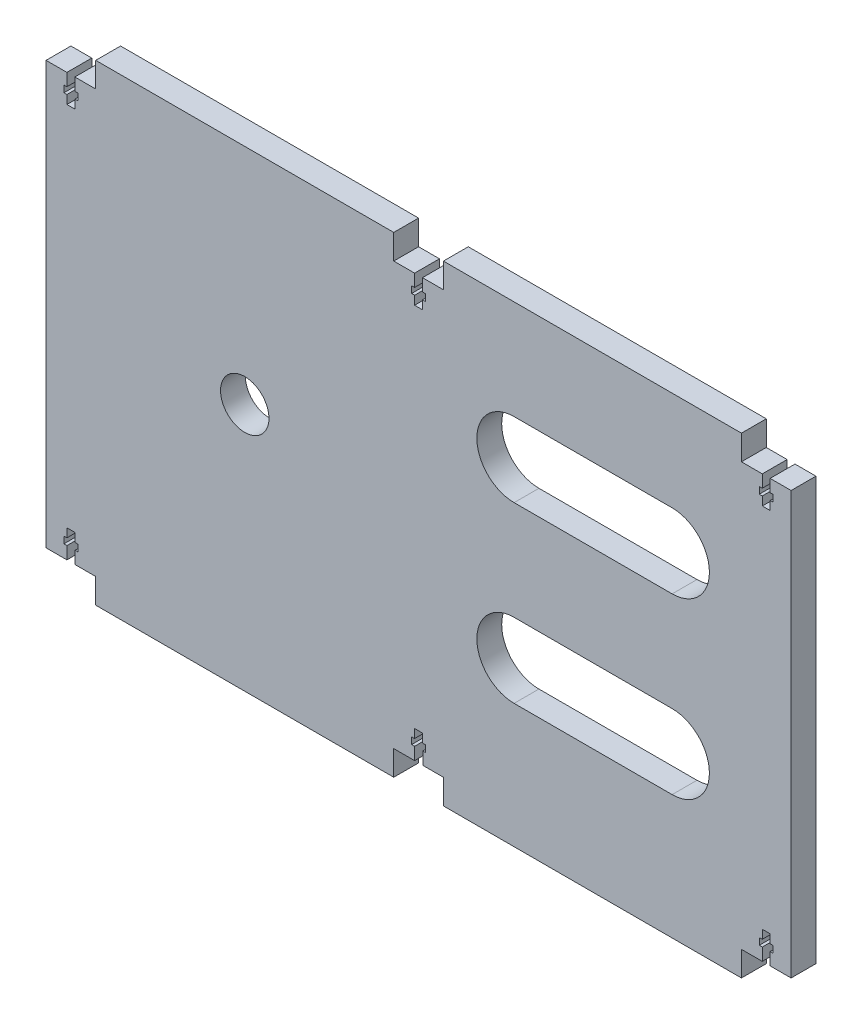
SolidWorks part; units mm, degrees
ref_plane "Ön Düzlem" through (0, 0, 0) normal (0, 0, 1) x (1, 0, 0)
ref_plane "Üst Düzlem" through (0, 0, 0) normal (0, 1, 0) x (1, 0, 0)
ref_plane "Sağ Düzlem" through (0, 0, 0) normal (1, 0, 0) x (0, 0, -1)
sketch "Çizim1" plane through (0, 0, 0) normal (0, 0, 1) x (1, 0, 0)
  line L1 (-150, -90) -> (150, -90)
  line L2 (-150, -90) -> (-150, 90)
  line L3 (-150, 90) -> (150, 90)
  line L4 (150, -90) -> (150, 90)
  line L5 (-150, -90) -> (150, 90) construction
  line L6 (-150, 90) -> (150, -90) construction
  circle A1 centre (-70, 10) radius 9.75
  point P0 (0, 0)
  dimension "D3" = 100
  dimension "D1" = 80
  dimension "D2" = 180
extrude "Yükseklik-Ekstrüzyon1" add sketch "Çizim1" along normal blind 10
sketch "Çizim2" plane through (0, 90, 0) normal (0, 1, 0) x (1, 0, 0)
  line L0 (130, -10) -> (130, 0)
  line L1 (130, -10) -> (10, -10)
  line L2 (130, 0) -> (10, 0)
  line L3 (10, -10) -> (10, 0)
  line L4 (150, -10) -> (-150, -10) construction
  line L5 (150, 0) -> (-150, 0) construction
  line L6 (150, -10) -> (150, 0) construction
  line L7 (-10, 0) -> (-10, -10)
  line L8 (-10, 0) -> (-130, 0)
  line L9 (-10, -10) -> (-130, -10)
  line L10 (-130, 0) -> (-130, -10)
  line L11 (-150, -10) -> (-150, 0) construction
  point P10 (0, 0)
  point P17 (0, 0)
  dimension "D1" = 20
  dimension "D2" = 10
  dimension "D3" = 20
  dimension "D4" = 10
extrude "Yükseklik-Ekstrüzyon2" add sketch "Çizim2" along normal blind 10
sketch "Çizim3" plane through (0, -90, 0) normal (0, -1, 0) x (-1, 0, 0)
  line L0 (150, -10) -> (150, 0)
  line L1 (150, -10) -> (130, -10)
  line L2 (150, 0) -> (130, 0)
  line L3 (130, -10) -> (130, 0)
  line L4 (-150, -10) -> (-150, 0)
  line L5 (-150, -10) -> (-130, -10)
  line L6 (-150, 0) -> (-130, 0)
  line L7 (-130, -10) -> (-130, 0)
  line L8 (10, 0) -> (10, -10)
  line L9 (10, 0) -> (-10, 0)
  line L10 (10, -10) -> (-10, -10)
  line L11 (-10, 0) -> (-10, -10)
  line L12 (150, 0) -> (-150, 0) construction
  line L13 (150, -10) -> (-150, -10) construction
  dimension "D1" = 120
  dimension "D2" = 20
  dimension "D3" = 20
  dimension "D4" = 20
extrude "Kes-Ekstrüzyon1" cut sketch "Çizim3" against normal blind 10
sketch "Çizim4" plane through (0, 0, 10) normal (0, 0, 1) x (1, 0, 0)
  line L0 (-142.8, 85) -> (-137.2, 85)
  line L1 (-142.8, 85) -> (-142.8, 82.3)
  line L2 (-137.2, 85) -> (-137.2, 82.3)
  line L3 (-142.8, 82.3) -> (-137.2, 82.3)
  line L4 (-130, 90) -> (-150, 90) construction
  line L5 (-10, 100) -> (-10, 90) construction
  line L6 (-2.8, 85) -> (2.8, 85)
  line L7 (-2.8, 85) -> (-2.8, 82.3)
  line L8 (-2.8, 82.3) -> (2.8, 82.3)
  line L9 (137.2, 85) -> (142.8, 85)
  line L10 (137.2, 85) -> (137.2, 82.3)
  line L11 (137.2, 82.3) -> (142.8, 82.3)
  line L12 (142.8, 85) -> (142.8, 82.3)
  line L13 (-130, -80) -> (-150, -80) construction
  line L14 (-142.8, -75) -> (-137.2, -75)
  line L15 (-142.8, -75) -> (-142.8, -72.3)
  line L16 (-142.8, -72.3) -> (-137.2, -72.3)
  line L17 (10, -80) -> (10, -90) construction
  line L18 (-2.8, -72.3) -> (2.8, -72.3)
  line L19 (-2.8, -72.3) -> (-2.8, -75)
  line L20 (-2.8, -75) -> (2.8, -75)
  line L21 (2.8, -72.3) -> (2.8, -75)
  line L22 (137.2, -72.3) -> (142.8, -72.3)
  line L23 (137.2, -72.3) -> (137.2, -75)
  line L24 (137.2, -75) -> (142.8, -75)
  line L25 (-150, 90) -> (-150, -80) construction
  line L27 (2.8, 85) -> (2.8, 82.3)
  line L28 (150, -80) -> (150, 90) construction
  line L29 (-137.2, -75) -> (-137.2, -72.3)
  line L30 (142.8, -72.3) -> (142.8, -75)
  dimension "D1" = 5
  dimension "D2" = 7.2
  dimension "D3" = 5.6
  dimension "D4" = 7.2
  dimension "D5" = 5.6
  dimension "D6" = 7.2
  dimension "D7" = 2.7
  dimension "D8" = 2.7
  dimension "D9" = 5
  dimension "D10" = 2.7
  dimension "D11" = 5.6
  dimension "D12" = 2.7
  dimension "D13" = 5.6
  dimension "D14" = 7.2
  dimension "D15" = 7.2
  dimension "D16" = 5.6
  dimension "D17" = 7.2
  dimension "D18" = 5.6
extrude "Kes-Ekstrüzyon2" cut sketch "Çizim4" against normal blind 10
sketch "Çizim5" plane through (0, 0, 10) normal (0, 0, 1) x (1, 0, 0)
  line L0 (-141.6, 82.3) -> (-138.4, 82.3)
  line L1 (-141.6, 82.3) -> (-141.6, 78.8)
  line L2 (-138.4, 82.3) -> (-138.4, 78.8)
  line L3 (-141.6, 78.8) -> (-138.4, 78.8)
  line L4 (-142.8, 82.3) -> (-137.2, 82.3) construction
  line L5 (-1.6, 82.3) -> (1.6, 82.3)
  line L6 (-1.6, 82.3) -> (-1.6, 78.8)
  line L7 (1.6, 82.3) -> (1.6, 78.8)
  line L8 (-1.6, 78.8) -> (1.6, 78.8)
  line L9 (-2.8, 82.3) -> (2.8, 82.3) construction
  line L10 (138.4, 82.3) -> (141.6, 82.3)
  line L11 (138.4, 82.3) -> (138.4, 78.8)
  line L12 (141.6, 82.3) -> (141.6, 78.8)
  line L13 (138.4, 78.8) -> (141.6, 78.8)
  line L14 (150, -80) -> (150, 90) construction
  line L15 (137.2, 82.3) -> (142.8, 82.3) construction
  line L16 (-141.6, -72.3) -> (-138.4, -72.3)
  line L17 (-141.6, -72.3) -> (-141.6, -68.8)
  line L18 (-138.4, -72.3) -> (-138.4, -68.8)
  line L19 (-141.6, -68.8) -> (-138.4, -68.8)
  line L20 (-137.2, -72.3) -> (-142.8, -72.3) construction
  line L21 (-1.6, -72.3) -> (1.6, -72.3)
  line L22 (-1.6, -72.3) -> (-1.6, -68.8)
  line L23 (1.6, -72.3) -> (1.6, -68.8)
  line L24 (-1.6, -68.8) -> (1.6, -68.8)
  line L25 (-1.6, 85) -> (-1.6, 90)
  line L26 (2.8, -72.3) -> (-2.8, -72.3) construction
  line L27 (138.4, -72.3) -> (141.6, -72.3)
  line L28 (138.4, -72.3) -> (138.4, -68.8)
  line L29 (141.6, -72.3) -> (141.6, -68.8)
  line L30 (138.4, -68.8) -> (141.6, -68.8)
  line L31 (-141.6, 85) -> (-138.4, 85)
  line L32 (142.8, -72.3) -> (137.2, -72.3) construction
  line L33 (-141.6, 85) -> (-141.6, 90.0914)
  line L34 (-138.4, 85) -> (-138.4, 90.0914)
  line L35 (-141.6, 90.0914) -> (-138.4, 90.0914)
  line L36 (-137.2, 85) -> (-142.8, 85) construction
  line L37 (-1.6, 85) -> (1.5689, 85)
  line L38 (-1.6, 90) -> (1.5689, 90)
  line L39 (1.5689, 85) -> (1.5689, 90)
  line L42 (2.8, 85) -> (-2.8, 85) construction
  line L43 (10, 90) -> (-10, 90) construction
  line L44 (138.4, 85) -> (138.4, 90)
  line L45 (138.4, 85) -> (141.5574, 85)
  line L46 (138.4, 90) -> (141.5574, 90)
  line L47 (141.5574, 85) -> (141.5574, 90)
  line L50 (142.8, 85) -> (137.2, 85) construction
  line L51 (150, 90) -> (130, 90) construction
  line L52 (138.4, -75) -> (138.4, -80)
  line L53 (138.4, -75) -> (141.5648, -75)
  line L54 (138.4, -80) -> (141.5648, -80)
  line L55 (141.5648, -75) -> (141.5648, -80)
  line L58 (137.2, -75) -> (142.8, -75) construction
  line L59 (150, -80) -> (130, -80) construction
  line L60 (-1.6, -75) -> (-1.6, -80)
  line L61 (-1.6, -75) -> (1.6832, -75)
  line L62 (-1.6, -80) -> (1.6832, -80)
  line L63 (1.6832, -75) -> (1.6832, -80)
  line L66 (-2.8, -75) -> (2.8, -75) construction
  line L67 (10, -80) -> (-10, -80) construction
  line L68 (-141.6, -75) -> (-141.6, -80)
  line L69 (-141.6, -75) -> (-138.3075, -75)
  line L70 (-141.6, -80) -> (-138.3075, -80)
  line L71 (-138.3075, -75) -> (-138.3075, -80)
  line L74 (-142.8, -75) -> (-137.2, -75) construction
  line L75 (-130, -80) -> (-150, -80) construction
  dimension "D1" = 3.2
  dimension "D2" = 1.2
  dimension "D3" = 3.5
  dimension "D4" = 3.5
  dimension "D5" = 3.2
  dimension "D6" = 1.2
  dimension "D7" = 1.2
  dimension "D8" = 3.2
  dimension "D9" = 3.5
  dimension "D10" = 3.5
  dimension "D11" = 3.2
  dimension "D12" = 1.2
  dimension "D13" = 3.5
  dimension "D14" = 1.2
  dimension "D15" = 3.5
  dimension "D16" = 8.4
  dimension "D17" = 3.2
extrude "Kes-Ekstrüzyon3" cut sketch "Çizim5" against normal blind 10
sketch "Çizim6" plane through (0, 0, 10) normal (0, 0, 1) x (1, 0, 0)
  line L1 (150, -80) -> (150, 90) construction
  line L2 (38.465, 45) -> (102.095, 45) construction
  line L3 (38.465, 60) -> (102.095, 60)
  line L4 (38.465, 30) -> (102.095, 30)
  line L5 (38.465, -25) -> (102.095, -25) construction
  line L6 (38.465, -40) -> (102.095, -40)
  line L7 (38.465, -10) -> (102.095, -10)
  line L8 (10, 100) -> (130, 100) construction
  line L9 (10, -90) -> (130, -90) construction
  arc A0 (38.465, 60) -> (38.465, 30) centre (38.465, 45) ccw
  arc A1 (102.095, 30) -> (102.095, 60) centre (102.095, 45) ccw
  arc A2 (38.465, -40) -> (38.465, -10) centre (38.465, -25) cw
  arc A3 (102.095, -10) -> (102.095, -40) centre (102.095, -25) cw
  point P7 (70.28, 45)
  point P14 (70.28, -25)
  point P21 (0, 0)
  dimension "D1" = 55
  dimension "D2" = 65
  dimension "D3" = 79.72
  dimension "D4" = 79.72
extrude "Kes-Ekstrüzyon4" cut sketch "Çizim6" against normal blind 10
